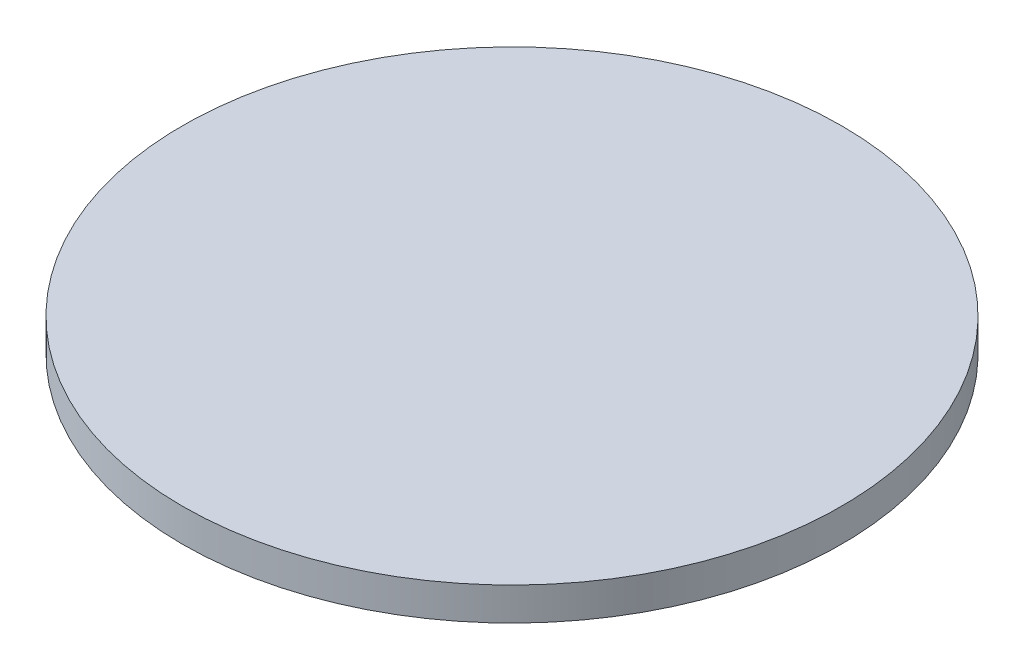
SolidWorks part; units mm, degrees
material "玻璃"
ref_plane "前视基准面" through (0, 0, 0) normal (0, 0, 1) x (1, 0, 0)
ref_plane "上视基准面" through (0, 0, 0) normal (0, 1, 0) x (1, 0, 0)
ref_plane "右视基准面" through (0, 0, 0) normal (1, 0, 0) x (0, 0, -1)
sketch "草图1" plane through (0, 0, 0) normal (0, 1, 0) x (1, 0, 0)
  circle A0 centre (0, 0) radius 20
  dimension "D1" = 40
extrude "凸台-拉伸1" add sketch "草图1" along normal blind 2
